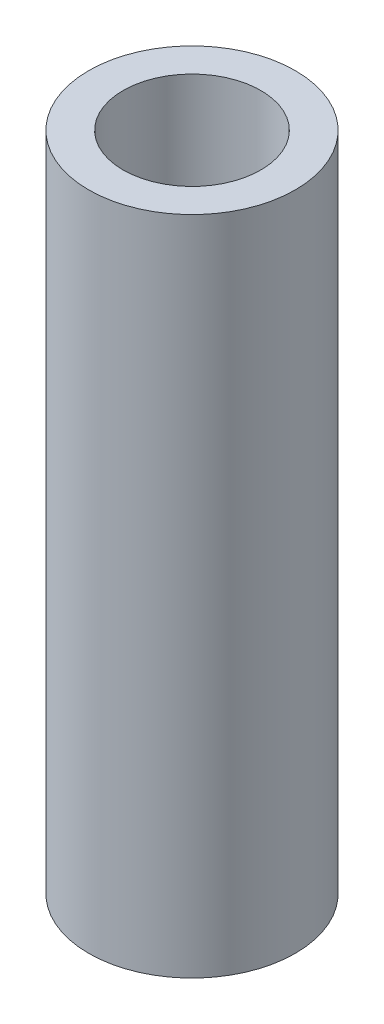
SolidWorks part; units mm, degrees
ref_plane "Front Plane" through (0, 0, 0) normal (0, 0, 1) x (1, 0, 0)
ref_plane "Top Plane" through (0, 0, 0) normal (0, 1, 0) x (1, 0, 0)
ref_plane "Right Plane" through (0, 0, 0) normal (1, 0, 0) x (0, 0, -1)
sketch "Sketch1" plane through (0, 0, 0) normal (0, 1, 0) x (1, 0, 0)
  circle A0 centre (0, 0) radius 9.525
  dimension "D1" = 19.05
extrude "Extrude1" add sketch "Sketch1" along normal blind 30.48 and the other way blind 30.48
sketch "Sketch2" plane through (0, 0, 0) normal (0, 1, 0) x (1, 0, 0)
  circle A0 centre (0, 0) radius 6.35
  dimension "D1" = 12.7
extrude "Cut-Extrude1" cut sketch "Sketch2" against normal through all and the other way through all
